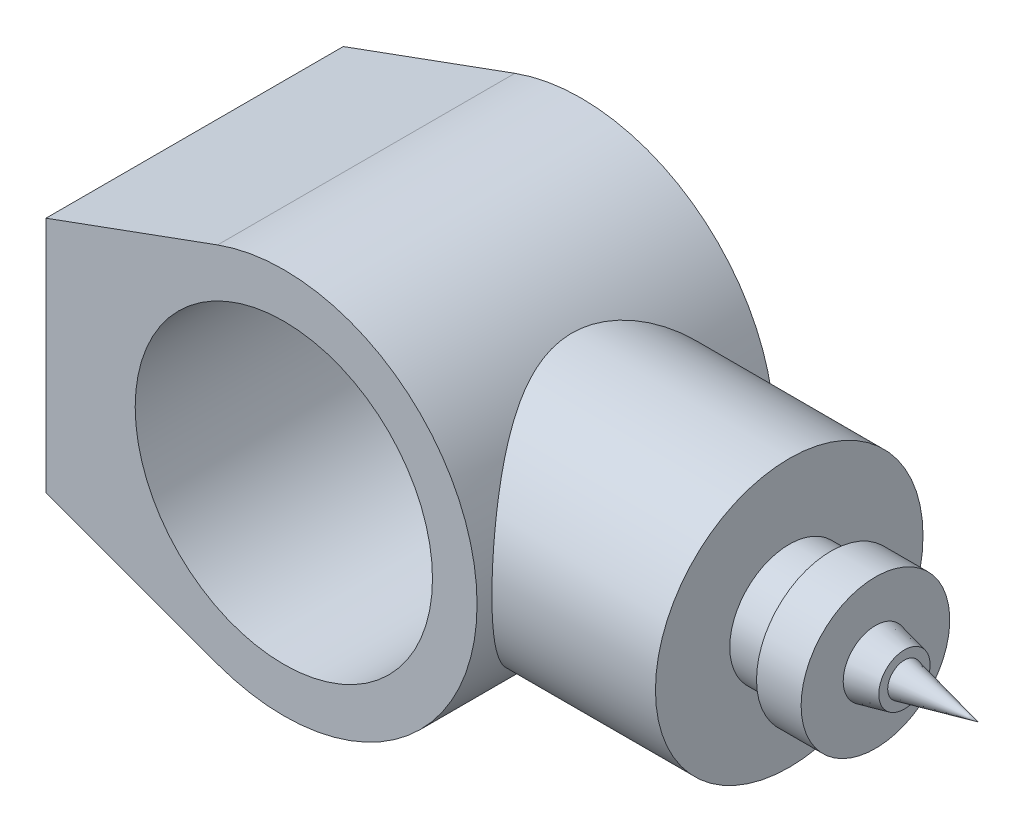
SolidWorks part; units mm, degrees
ref_plane "Front Plane" through (0, 0, 0) normal (0, 0, 1) x (1, 0, 0)
ref_plane "Top Plane" through (0, 0, 0) normal (0, 1, 0) x (1, 0, 0)
ref_plane "Right Plane" through (0, 0, 0) normal (1, 0, 0) x (0, 0, -1)
sketch "Sketch1" plane through (0, 0, 0) normal (0, 0, 1) x (1, 0, 0)
  line L0 (-80, 40) -> (-80, -40)
  line L1 (-80, 40) -> (-22.2817, 61.0617)
  line L2 (-80, -40) -> (-22.2817, -61.0617)
  arc A0 (-22.2817, -61.0617) -> (-22.2817, 61.0617) centre (0, 0) ccw
  circle A1 centre (0, 0) radius 50
  point P7 (-80, 0)
  dimension "D1" = 80
  dimension "D2" = 100
  dimension "D3" = 130
  dimension "D4" = 80
extrude "Boss-Extrude1" add sketch "Sketch1" along normal mid plane 100
ref_plane "Plane1" through (120, 0, 0) normal (1, 0, 0) x (0, 0, -1)
sketch "Sketch2" plane through (120, 0, 0) normal (1, 0, 0) x (0, 0, -1)
  circle A0 centre (0, 0) radius 45
extrude "Boss-Extrude2" add sketch "Sketch2" against normal up to next
sketch "Sketch4" plane through (0, 0, 0) normal (0, 0, 1) x (1, 0, 0)
  line L0 (0, 0) -> (341.4778, 0) construction
  line L1 (120, 0) -> (120, -20)
  line L2 (120, -45) -> (120, 45) construction
  line L3 (120, -20) -> (134, -20)
  line L4 (134, -20) -> (134, -25)
  line L5 (134, -25) -> (149, -25)
  line L6 (149, -25) -> (149, -10.8455)
  line L7 (149, -10.8455) -> (158.751, -8.628)
  line L8 (158.751, -8.628) -> (158.751, -5.628)
  line L9 (158.751, -5.628) -> (183.4986, 0)
  line L10 (183.4986, 0) -> (120, 0)
  point P15 (141.5, -25)
  dimension "D1" = 20
  dimension "D2" = 14
  dimension "D3" = 5
  dimension "D4" = 15
  dimension "D5" = 10
  dimension "D6" = 25.3795
  dimension "D7" = 63.4986
  dimension "D8" = 3
revolve "Revolve1" add sketch "Sketch4" angle 360 about L0
